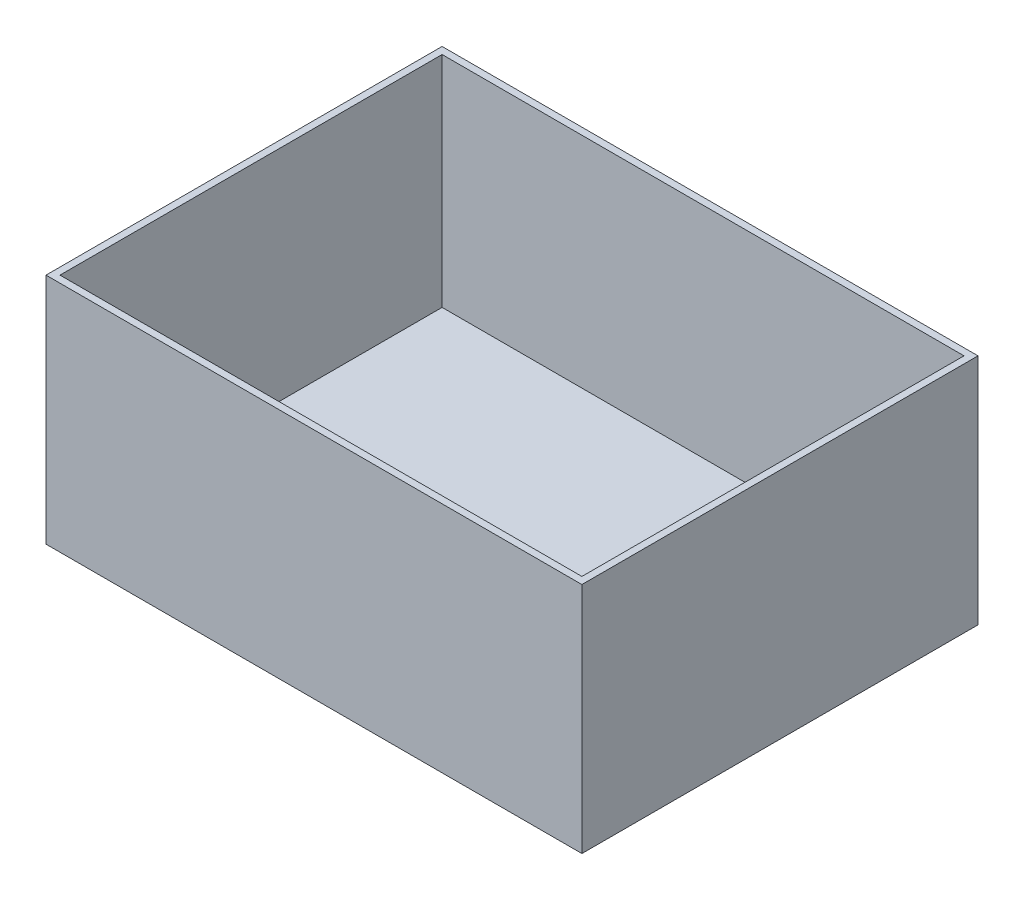
SolidWorks part; units mm, degrees
ref_plane "Přední rovina" through (0, 0, 0) normal (0, 0, 1) x (1, 0, 0)
ref_plane "Horní rovina" through (0, 0, 0) normal (0, 1, 0) x (1, 0, 0)
ref_plane "Pravá rovina" through (0, 0, 0) normal (1, 0, 0) x (0, 0, -1)
sketch "Skica5" plane through (0, 0, 0) normal (0, 0, 1) x (1, 0, 0)
  line L1 (-115, 50) -> (115, 50)
  line L2 (-115, 50) -> (-115, -50)
  line L3 (-115, -50) -> (115, -50)
  line L4 (115, 50) -> (115, -50)
  line L5 (-115, 50) -> (115, -50) construction
  line L6 (-115, -50) -> (115, 50) construction
  point P0 (0, 0)
  dimension "D1" = 100
  dimension "D2" = 230
extrude "Přidat vysunutím3" add sketch "Skica5" along normal blind 170
sketch "Skica8" plane through (0, 50, 0) normal (0, 1, 0) x (1, 0, 0)
  line L0 (115, -170) -> (115, 0) construction
  line L1 (112, -167) -> (-112, -167)
  line L2 (112, -167) -> (112, -3)
  line L3 (112, -3) -> (-112, -3)
  line L4 (-112, -167) -> (-112, -3)
  line L5 (112, -167) -> (-112, -3) construction
  line L6 (112, -3) -> (-112, -167) construction
  line L7 (115, 0) -> (-115, 0) construction
  point P0 (0, -85)
  dimension "D1" = 164
  dimension "D2" = 224
  dimension "D3" = 3
  dimension "D4" = 3
extrude "Odebrat vysunutím3" cut sketch "Skica8" against normal blind 94
